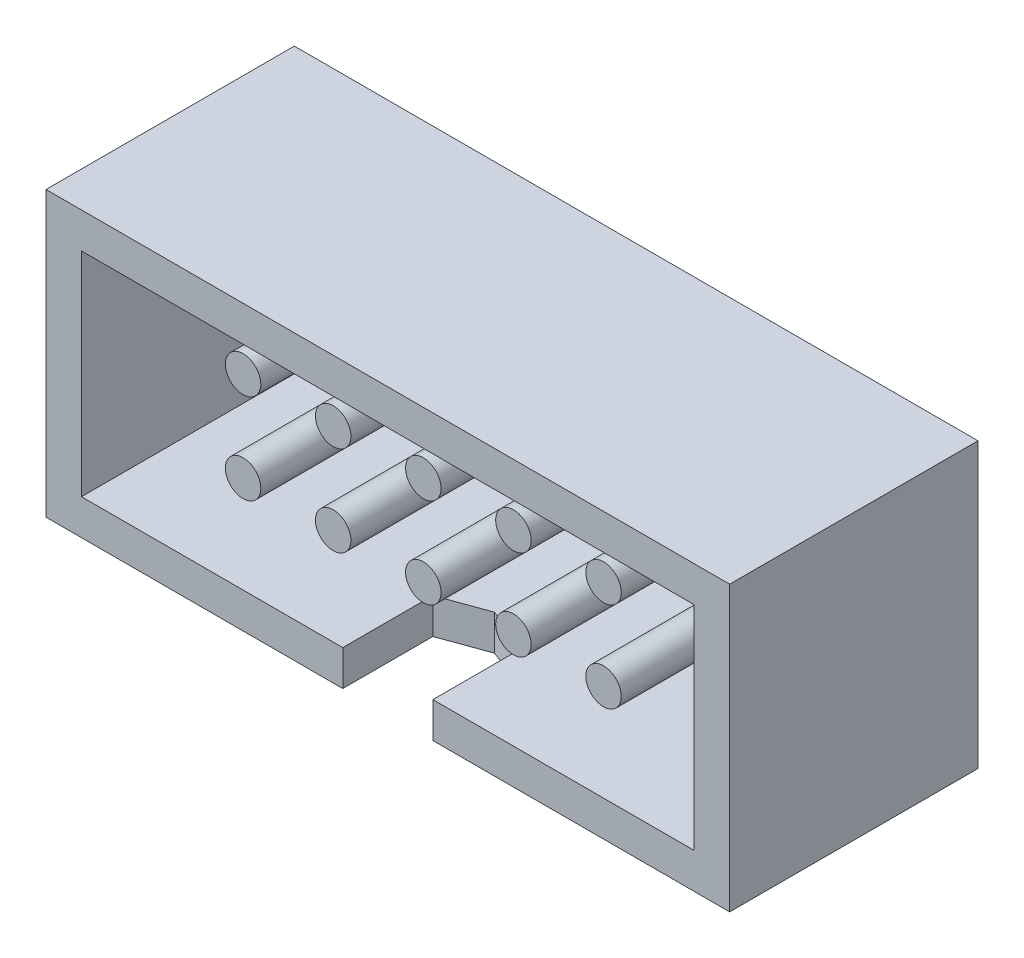
SolidWorks part; units mm, degrees
ref_plane "前视基准面" through (0, 0, 0) normal (0, 0, 1) x (1, 0, 0)
ref_plane "上视基准面" through (0, 0, 0) normal (0, 1, 0) x (1, 0, 0)
ref_plane "右视基准面" through (0, 0, 0) normal (1, 0, 0) x (0, 0, -1)
sketch "草图1" plane through (0, 0, 0) normal (0, 0, 1) x (1, 0, 0)
  line L1 (0, 0) -> (19.27, 0)
  line L2 (0, 0) -> (0, -8)
  line L3 (0, -8) -> (19.27, -8)
  line L4 (19.27, 0) -> (19.27, -8)
  dimension "D1" = 19.27
  dimension "D2" = 8
extrude "凸台-拉伸1" add sketch "草图1" along normal blind 7
sketch "草图2" plane through (0, 0, 7) normal (0, 0, 1) x (1, 0, 0)
  line L0 (1, -1) -> (18.27, -1)
  line L1 (19.27, 0) -> (0, 0) construction
  line L2 (1, -1) -> (1, -7)
  line L3 (0, 0) -> (0, -8) construction
  line L4 (1, -7) -> (18.27, -7)
  line L5 (0, -8) -> (19.27, -8) construction
  line L6 (18.27, -1) -> (18.27, -7)
  line L7 (19.27, -8) -> (19.27, 0) construction
  point P14 (19.27, -4)
  dimension "D1" = 1
  dimension "D2" = 1
  dimension "D3" = 1
  dimension "D4" = 1
extrude "切除-拉伸1" cut sketch "草图2" against normal blind 6
sketch "草图3" plane through (0, -8, 0) normal (0, -1, 0) x (1, 0, 0)
  line L0 (9.635, 7) -> (9.635, 0) construction
  line L1 (0, 7) -> (19.27, 7) construction
  line L2 (0, 0) -> (19.27, 0) construction
  line L3 (8.365, 7) -> (8.365, 4.46)
  line L4 (10.905, 7) -> (10.905, 4.46)
  line L5 (8.365, 7) -> (10.905, 7)
  line L6 (8.365, 4.46) -> (9.635, 4)
  line L7 (9.635, 4) -> (10.905, 4.46)
  dimension "D1" = 2.54
  dimension "D2" = 2.54
extrude "切除-拉伸2" cut sketch "草图3" against normal up to next
sketch "草图4" plane through (0, 0, 1) normal (0, 0, 1) x (1, 0, 0)
  line L0 (1, -4) -> (18.27, -4) construction
  line L1 (1, -1) -> (1, -7) construction
  line L2 (18.27, -7) -> (18.27, -1) construction
  line L3 (9.635, -1) -> (9.635, -7) construction
  line L4 (18.27, -1) -> (1, -1) construction
  line L5 (1, -7) -> (18.27, -7) construction
  circle A0 centre (9.635, -2.73) radius 0.5
  circle A1 centre (12.175, -2.73) radius 0.5
  circle A2 centre (14.715, -2.73) radius 0.5
  circle A3 centre (4.555, -2.73) radius 0.5
  circle A4 centre (7.095, -2.73) radius 0.5
  circle A5 centre (14.715, -5.27) radius 0.5
  circle A6 centre (12.175, -5.27) radius 0.5
  circle A7 centre (9.635, -5.27) radius 0.5
  circle A8 centre (7.095, -5.27) radius 0.5
  circle A9 centre (4.555, -5.27) radius 0.5
  dimension "D1" = 1
  dimension "D2" = 2.54
  dimension "D3" = 3
extrude "凸台-拉伸2" add sketch "草图4" along normal blind 5 and the other way blind 3
